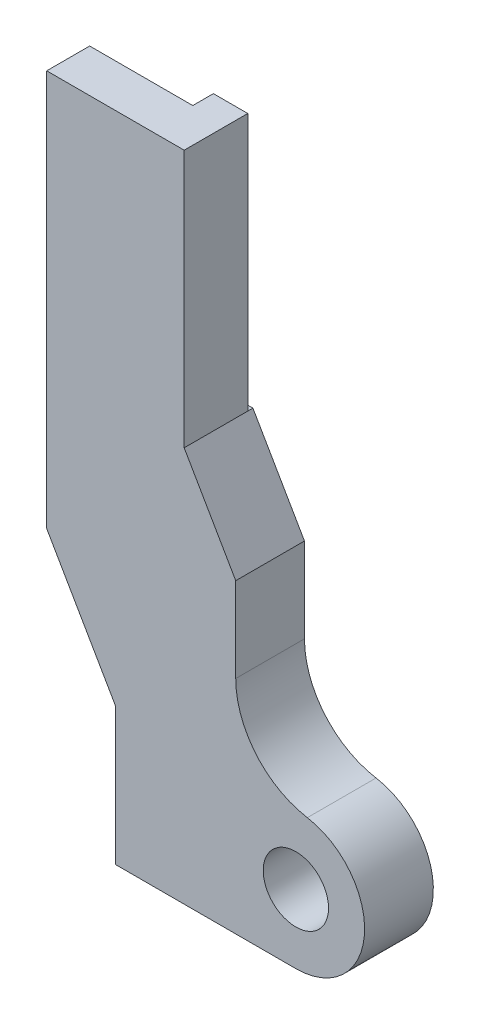
SolidWorks part; units mm, degrees
ref_plane "前视基准面" through (0, 0, 0) normal (0, 0, 1) x (1, 0, 0)
ref_plane "上视基准面" through (0, 0, 0) normal (0, 1, 0) x (1, 0, 0)
ref_plane "右视基准面" through (0, 0, 0) normal (1, 0, 0) x (0, 0, -1)
sketch "草图1" plane through (0, 0, 0) normal (0, 0, 1) x (1, 0, 0)
  line L0 (0, 4) -> (-10.5, 4)
  line L1 (-10.5, 4) -> (-10.5, -4)
  line L2 (-10.5, -4) -> (0, -4)
  circle A0 centre (0, 0) radius 1.9
  arc A1 (0, -4) -> (0, 4) centre (0, 0) ccw
  dimension "D1" = 3.8
  dimension "D2" = 8
  dimension "D3" = 10.5
extrude "凸台-拉伸1" add sketch "草图1" along normal blind 4
sketch "草图2" plane through (0, 4, 0) normal (0, 1, 0) x (1, 0, 0)
  line L0 (0, 0) -> (-10.5, 0) construction
  line L1 (-7.5, 0) -> (-4.5, 0)
  line L2 (-7.5, 0) -> (-7.5, -1.5)
  line L3 (-7.5, -1.5) -> (-4.5, -1.5)
  line L4 (-4.5, 0) -> (-4.5, -1.5)
  line L5 (-10.5, -4) -> (-10.5, 0) construction
  dimension "D1" = 3
  dimension "D2" = 3
  dimension "D3" = 1.5
extrude "切除-拉伸1" cut sketch "草图2" against normal through all
sketch "草图3" plane through (0, 0, 0) normal (0, 0, -1) x (-1, 0, 0)
  line L0 (10.5, -4) -> (7.5, -4) construction
  line L1 (10.5, 4) -> (9.5, 4)
  line L2 (10.5, 4) -> (10.5, -4)
  line L3 (10.5, -4) -> (9.5, -4)
  line L4 (9.5, 4) -> (9.5, -4)
  dimension "D1" = 1
extrude "凸台-拉伸2" add sketch "草图3" along normal blind 1
sketch "草图4" plane through (0, 0, 4) normal (0, 0, 1) x (1, 0, 0)
  line L0 (0, 4) -> (-10.5, 4) construction
  line L1 (-5, 4) -> (-10.5, 4)
  line L2 (-5, 4) -> (-5, 34)
  line L3 (-5, 34) -> (-10.5, 34)
  line L4 (-10.5, 4) -> (-10.5, 34)
  line L5 (-10.5, 4) -> (-10.5, -4) construction
  circle A0 centre (0, 0) radius 1.9 construction
  dimension "D1" = 5
  dimension "D2" = 30
extrude "凸台-拉伸3" add sketch "草图4" against normal up to surface (2.5 mm away) up to face at (-6, 0, 1.5)
sketch "草图5" plane through (0, 4, 0) normal (0, 1, 0) x (1, 0, 0)
  line L0 (-5, -4) -> (-3.5, -4)
  line L1 (0, -4) -> (-5, -4) construction
  line L2 (-3.5, -4) -> (-3.5, 0)
  line L3 (0, 0) -> (-4.5, 0) construction
  line L4 (-3.5, 0) -> (-4.5, 0)
  line L5 (-4.5, 0) -> (-4.5, -1.5)
  line L6 (-4.5, -1.5) -> (-5, -1.5)
  line L7 (-5, -1.5) -> (-5, -4)
  dimension "D1" = 1.5
extrude "凸台-拉伸4" add sketch "草图5" along normal blind 15
sketch "草图6" plane through (0, 19, 0) normal (0, 1, 0) x (1, 0, 0)
  line L0 (-8.5, -1.5) -> (-8.5, -0.3)
  line L1 (-10.5, -1.5) -> (-5, -1.5) construction
  line L2 (-8.5, -0.3) -> (-6.5, -0.3)
  line L3 (-6.5, -0.3) -> (-6.5, -1.5)
  line L4 (-6.5, -1.5) -> (-8.5, -1.5)
  line L5 (-4.5, 0) -> (-4.5, -1.5) construction
  dimension "D1" = 2
  dimension "D2" = 4
  dimension "D3" = 1.2
extrude "凸台-拉伸5" add sketch "草图6" along normal up to surface (15 mm away) up to face at (-7.75, 34, 2.75)
sketch "草图7" plane through (0, 0, 1.5) normal (0, 0, -1) x (-1, 0, 0)
  line L0 (8.5, 19) -> (4.5, 12.0718)
  line L1 (4.5, -4) -> (4.5, 19) construction
  line L2 (4.5, 12.0718) -> (4.5, 19)
  line L3 (4.5, 19) -> (8.5, 19)
  dimension "D1" = 30
extrude "凸台-拉伸6" add sketch "草图7" along normal up to surface (1.5 mm away) up to face at (-8.5, 0, 0)
sketch "草图8" plane through (0, 0, 0) normal (0, 0, -1) x (-1, 0, 0)
  line L0 (6.5, 34) -> (6.5, 19)
  line L1 (6.5, 19) -> (3.5, 13.8038)
  line L2 (3.5, 19) -> (3.5, 4) construction
  line L3 (3.5, 13.8038) -> (3.5, 19)
  line L4 (3.5, 19) -> (5, 19)
  line L5 (5, 19) -> (5, 34)
  line L6 (5, 34) -> (6.5, 34)
  line L7 (8.5, 19) -> (4.5, 12.0718) construction
extrude "切除-拉伸2" cut sketch "草图8" against normal up to next
sketch "草图9" plane through (0, 0, 4) normal (0, 0, 1) x (1, 0, 0)
  line L0 (-10.5, 34) -> (-14.5, 34)
  line L1 (-14.5, 34) -> (-14.5, 10.9282)
  line L2 (-14.5, 10.9282) -> (-10.5, 4)
  line L3 (-10.5, 34) -> (-10.5, -4) construction
  line L4 (-10.5, 4) -> (-10.5, 34)
  line L5 (-8.5, 19) -> (-4.5, 12.0718) construction
  dimension "D1" = 4
extrude "凸台-拉伸7" add sketch "草图9" against normal up to surface (2.5 mm away) up to face at (-7.75, 12.384, 1.5)
sketch "草图10" plane through (0, 0, 1.5) normal (0, 0, -1) x (-1, 0, 0)
  line L0 (8.5, 4) -> (13, 11.7942)
  line L1 (13, 11.7942) -> (13, 34)
  line L2 (14.5, 34) -> (8.5, 34) construction
  line L3 (13, 34) -> (14.5, 34)
  line L4 (14.5, 34) -> (14.5, 10.9282)
  line L5 (14.5, 10.9282) -> (10.5, 4)
  line L6 (10.5, 4) -> (8.5, 4)
  dimension "D1" = 1.5
  dimension "D2" = 2
extrude "凸台-拉伸8" add sketch "草图10" along normal up to surface (2.5 mm away) up to face at (-10, 0, -1)
sketch "草图11" plane through (0, 0, -1) normal (0, 0, -1) x (-1, 0, 0)
  line L0 (13, 34) -> (13, 11.7942) construction
  line L1 (14.5, 34) -> (13, 34)
  line L2 (14.5, 34) -> (14.5, 24)
  line L3 (14.5, 24) -> (13, 24)
  line L4 (13, 34) -> (13, 24)
  dimension "D1" = 10
extrude "切除-拉伸3" cut sketch "草图11" against normal up to surface (2.5 mm away) up to face at (-8.3889, 12.3184, 1.5)
sketch "草图12" plane through (0, 4, 0) normal (0, -1, 0) x (1, 0, 0)
  line L4 (-8.5, -1) -> (-8.5, 0)
  line L5 (-8.5, 0) -> (-9.5, 0)
  line L6 (-9.5, 0) -> (-9.5, -1)
  line L7 (-9.5, -1) -> (-8.5, -1)
  line L8 (-8.5, -1) -> (-8.5, 0)
  line L9 (-8.5, 0) -> (-9.5, 0)
  line L10 (-9.5, 0) -> (-9.5, -1)
  line L11 (-9.5, -1) -> (-8.5, -1)
  dimension "D1" = 0
extrude "切除-拉伸4" cut sketch "草图12" against normal up to surface (1.7321 mm away)
fillet "圆角1" radius 5 1 edges at (-3.5, 4, 2)
